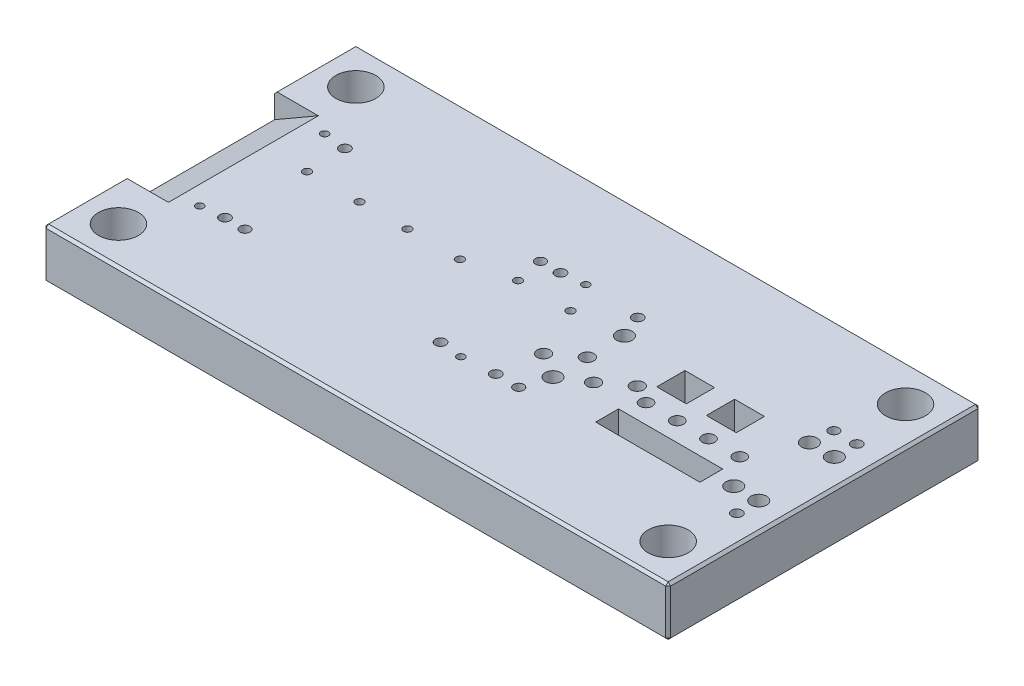
SolidWorks part; units mm, degrees
material "Plain Carbon Steel"
ref_plane "Front Plane" through (0, 0, 0) normal (0, 0, 1) x (1, 0, 0)
ref_plane "Top Plane" through (0, 0, 0) normal (0, 1, 0) x (1, 0, 0)
ref_plane "Right Plane" through (0, 0, 0) normal (1, 0, 0) x (0, 0, -1)
sketch "Sketch1" plane through (0, 0, 0) normal (0, 1, 0) x (1, 0, 0)
  line L1 (-250, -125) -> (250, -125)
  line L2 (-250, -125) -> (-250, 125)
  line L3 (-250, 125) -> (250, 125)
  line L4 (250, -125) -> (250, 125)
  line L5 (-250, -125) -> (250, 125) construction
  line L6 (-250, 125) -> (250, -125) construction
  point P0 (0, 0)
  dimension "D1" = 500
  dimension "D2" = 250
extrude "Boss-Extrude1" add sketch "Sketch1" against normal blind 40
hole_wizard "Ø32.0 (32) Diameter Hole1" positions "Sketch6" profile "Sketch4" hole size "Ø1.0" standard "ISO" end condition through all
sketch "Sketch6" plane through (0, 0, 0) normal (0, 1, 0) x (1, 0, 0)
  line L0 (-250, 125) -> (-250, -125) construction
  line L1 (250, 125) -> (-250, 125) construction
  line L2 (-250, -125) -> (250, -125) construction
  line L3 (250, -125) -> (250, 125) construction
  point P0 (-220, 95)
  point P2 (-220, -95)
  point P4 (220, -95)
  point P6 (220, 95)
  dimension "D1" = 30
  dimension "D2" = 30
  dimension "D3" = 30
  dimension "D4" = 30
sketch "Sketch4" plane through (-220, 0, -95) normal (1, 0, 0) x (0, 0, 1)
  line L0 (0, 0) -> (0, 40)
  line L1 (0, 40) -> (16, 40)
  line L2 (16, 40) -> (16, 0)
  line L5 (16, 0) -> (0, 0)
  line L11 (0, -6.35) -> (0, 107.95) construction
  dimension "Thru Hole Dia." = 32
  dimension "Thru Hole Depth" = 40
chamfer "Chamfer1" distance 2 angle 45 12 edges at (250, -40, 0) (250, 0, 0) (0, -40, -125) (250, -20, -125) (0, 0, -125) (-250, -40, 0) (-250, -20, -125) (-250, 0, 0) (250, -20, 125) (0, -40, 125) (-250, -20, 125) (0, 0, 125)
hole_wizard "CBORE for M8 Hex Socket Head Cap Screw1" positions "Sketch10" profile "Sketch8" counterbore size "M8" standard "ISO" end condition through all
sketch "Sketch10" plane through (0, -40, 0) normal (0, -1, 0) x (-1, 0, 0)
  point P0 (-228, 48)
  point P3 (-52.6325, 48)
  point P6 (-228, -48)
  point P9 (-35, -48)
  point P12 (9.219, 48)
  point P15 (181.75, 48)
  point P18 (181.75, -48)
  point P22 (9.219, -48)
sketch "Sketch8" plane through (228, -40, -48) normal (1, 0, 0) x (0, 0, -1)
  line L0 (0, 0) -> (0, 40)
  line L1 (0, 40) -> (4.2, 40)
  line L3 (4.2, 40) -> (4.2, 8.6)
  line L4 (4.2, 8.6) -> (7.5, 8.6)
  line L5 (7.5, 8.6) -> (7.5, 0)
  line L7 (7.5, 0) -> (0, 0)
  line L11 (0, -6.35) -> (0, 107.95) construction
  dimension "Thru Hole Dia." = 8.4
  dimension "Thru Hole Depth" = 40
  dimension "C'Bore Dia." = 15
  dimension "C'Bore Depth" = 8.6
hole_wizard "Ø8.0mm Dowel Hole1" positions "Sketch13" profile "Sketch12" hole size "Ø8.0" standard "ISO" end condition through all
sketch "Sketch13" plane through (0, -40, 0) normal (0, -1, 0) x (-1, 0, 0)
  point P0 (-53.4, -48)
  point P3 (-209.6, 48)
  point P6 (25.219, 48)
  point P9 (165.75, -48)
sketch "Sketch12" plane through (53.4, -40, 48) normal (1, 0, 0) x (0, 0, -1)
  line L0 (0, 0) -> (0, 40)
  line L1 (0, 40) -> (4, 40)
  line L2 (4, 40) -> (4, 0)
  line L5 (4, 0) -> (0, 0)
  line L11 (0, -6.35) -> (0, 107.95) construction
  dimension "Thru Hole Dia." = 8
  dimension "Thru Hole Depth" = 40
sketch "Sketch16" plane through (0, 0, 0) normal (0, 1, 0) x (1, 0, 0)
  circle A0 centre (60, 30) radius 6.25 construction
  circle A1 centre (208, 30) radius 6.25 construction
  circle A2 centre (228, 30) radius 6.25 construction
  circle A3 centre (228, -30.5) radius 6.25 construction
  circle A4 centre (208, -30.5) radius 6.25 construction
  circle A5 centre (190, -7.72) radius 5 construction
  circle A6 centre (165, -7.72) radius 5 construction
  circle A7 centre (140, -7.72) radius 5 construction
  circle A8 centre (115, -7.72) radius 5 construction
  circle A9 centre (60, -27.22) radius 6.25 construction
  circle A10 centre (60, 30) radius 6.25
  circle A11 centre (208, 30) radius 6.25
  circle A12 centre (228, 30) radius 6.25
  circle A13 centre (228, -30.5) radius 6.25
  circle A14 centre (208, -30.5) radius 6.25
  circle A15 centre (190, -7.72) radius 5
  circle A16 centre (165, -7.72) radius 5
  circle A17 centre (140, -7.72) radius 5
  circle A18 centre (115, -7.72) radius 5
  circle A19 centre (60, -27.22) radius 6.25
extrude "Cut-Extrude1" cut sketch "Sketch16" against normal blind 10
sketch "Sketch18" plane through (0, 0, 0) normal (0, 1, 0) x (1, 0, 0)
  circle A0 centre (-200, -50) radius 3
  circle A1 centre (-200, 50) radius 3
  circle A2 centre (9.031, 50) radius 3
  circle A3 centre (9.031, -50) radius 3
  dimension "D1" = 6
extrude "Cut-Extrude2" cut sketch "Sketch18" against normal up to next
sketch "Sketch19" plane through (0, -40, 0) normal (0, -1, 0) x (1, 0, 0)
  circle A0 centre (-200, 50) radius 5.5
  circle A1 centre (-200, -50) radius 5.5
  circle A2 centre (9.031, -50) radius 5.5
  circle A3 centre (9.031, 50) radius 5.5
  dimension "D1" = 11
extrude "Cut-Extrude3" cut sketch "Sketch19" against normal blind 33
hole_wizard "CBORE for M6 Hex Socket Head Cap Screw1" positions "Sketch22" profile "Sketch21" counterbore size "M6" standard "ISO" end condition through all
sketch "Sketch22" plane through (0, -40, 0) normal (0, -1, 0) x (-1, 0, 0)
  point P0 (-21.125, 25.691)
  point P3 (20.875, 25.691)
  point P6 (58.875, 17.1524)
  point P9 (100.875, 17.1524)
  point P12 (138.875, 16.78)
  point P15 (180.875, 16.78)
sketch "Sketch21" plane through (21.125, -40, -25.691) normal (1, 0, 0) x (0, 0, -1)
  line L0 (0, 0) -> (0, 40)
  line L1 (0, 40) -> (3.2, 40)
  line L3 (3.2, 40) -> (3.2, 6.4)
  line L4 (3.2, 6.4) -> (5.5, 6.4)
  line L5 (5.5, 6.4) -> (5.5, 0)
  line L7 (5.5, 0) -> (0, 0)
  line L11 (0, -6.35) -> (0, 107.95) construction
  dimension "Thru Hole Dia." = 6.4
  dimension "Thru Hole Depth" = 40
  dimension "C'Bore Dia." = 11
  dimension "C'Bore Depth" = 6.4
sketch "Sketch23" plane through (0, -40, 0) normal (0, -1, 0) x (1, 0, 0)
  line L8 (191.7023, 23.0177) -> (191.7023, 41.3023)
  line L9 (191.7023, 41.3023) -> (108.2977, 41.3023)
  line L10 (108.2977, 41.3023) -> (108.2977, 23.0177)
  line L11 (108.2977, 23.0177) -> (191.7023, 23.0177)
  line L12 (191.7023, 23.0177) -> (191.7023, 41.3023)
  line L13 (191.7023, 41.3023) -> (108.2977, 41.3023)
  line L14 (108.2977, 41.3023) -> (108.2977, 23.0177)
  line L15 (108.2977, 23.0177) -> (191.7023, 23.0177)
  line L20 (171.9523, -30.1423) -> (171.9523, -7.5777)
  line L21 (148.0477, -30.1423) -> (171.9523, -30.1423)
  line L22 (148.0477, -7.5777) -> (148.0477, -30.1423)
  line L23 (171.9523, -7.5777) -> (148.0477, -7.5777)
  line L24 (171.9523, -30.1423) -> (171.9523, -7.5777)
  line L25 (148.0477, -30.1423) -> (171.9523, -30.1423)
  line L26 (148.0477, -7.5777) -> (148.0477, -30.1423)
  line L27 (171.9523, -7.5777) -> (148.0477, -7.5777)
  line L32 (108.2977, -30.1423) -> (131.9523, -30.1423)
  line L33 (108.2977, -7.5777) -> (108.2977, -30.1423)
  line L34 (131.9523, -7.5777) -> (108.2977, -7.5777)
  line L35 (131.9523, -30.1423) -> (131.9523, -7.5777)
  line L36 (108.2977, -30.1423) -> (131.9523, -30.1423)
  line L37 (108.2977, -7.5777) -> (108.2977, -30.1423)
  line L38 (131.9523, -7.5777) -> (108.2977, -7.5777)
  line L39 (131.9523, -30.1423) -> (131.9523, -7.5777)
  circle A404 centre (100, -0.28) radius 5.1746
  circle A405 centre (100, -0.28) radius 5.1746
  circle A407 centre (80, 14.72) radius 5.1746
  circle A408 centre (80, 14.72) radius 5.1746
  circle A410 centre (60, -0.28) radius 5.1746
  circle A411 centre (60, -0.28) radius 5.1746
  circle A413 centre (40, 14.72) radius 5.1746
  circle A414 centre (40, 14.72) radius 5.1746
  dimension "D1" = 1
  dimension "D2" = 1
  dimension "D3" = 1
  dimension "D4" = 1
  dimension "D5" = 1
  dimension "D6" = 1
  dimension "D7" = 1
extrude "Cut-Extrude4" cut sketch "Sketch23" against normal up to next
sketch "Sketch24" plane through (0, 0, 0) normal (0, 1, 0) x (1, 0, 0)
  line L0 (-215, -60) -> (-215, 60)
  line L4 (-22, 0) -> (22, 0) construction
  line L5 (-250, -123) -> (-250, 123) construction
  point P2 (-215, 0)
  dimension "D1" = 120
  dimension "D2" = 35
sketch "Sketch25" plane through (0, 0, 0) normal (0, 0, 1) x (1, 0, 0)
  line L0 (-215, 0) -> (-250, -20.2073)
  line L1 (-250, -20.2073) -> (-250, 0)
  line L2 (-250, 0) -> (-215, 0)
  line L3 (-250, -38) -> (-250, -2) construction
  point P0 (-215, 0)
  dimension "D1" = 30
sweep "Cut-Sweep1" cut profiles "Sketch25" path "Sketch24"
